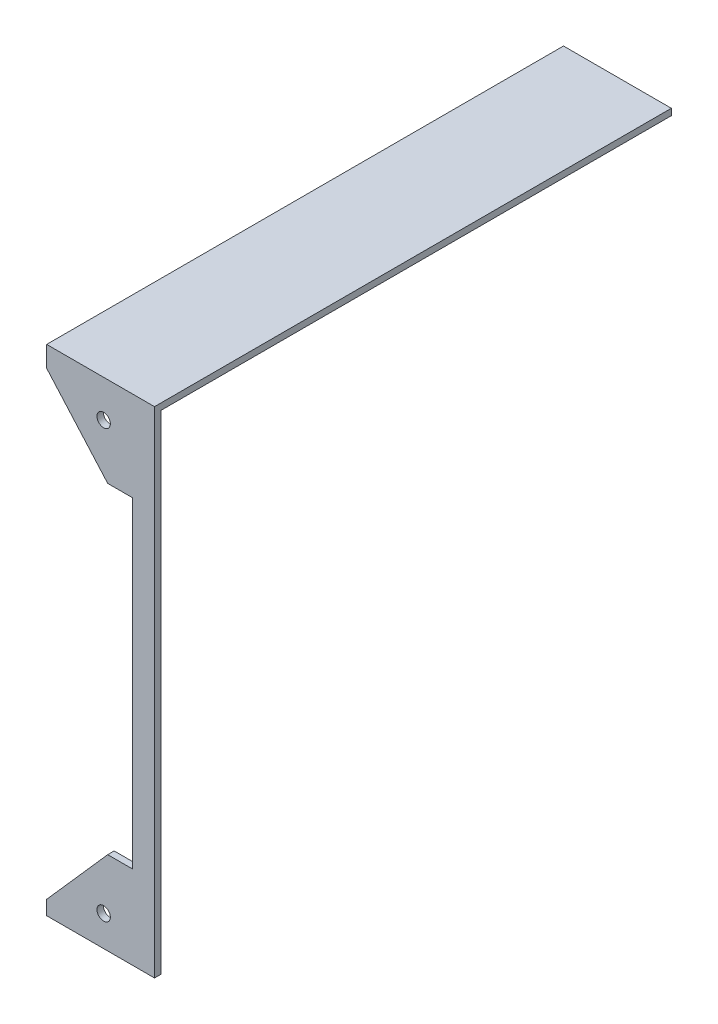
SolidWorks part; units mm, degrees
ref_plane "Front Plane" through (0, 0, 0) normal (0, 0, 1) x (1, 0, 0)
ref_plane "Top Plane" through (0, 0, 0) normal (0, 1, 0) x (1, 0, 0)
ref_plane "Right Plane" through (0, 0, 0) normal (1, 0, 0) x (0, 0, -1)
sketch "Sketch1" plane through (0, 0, 0) normal (0, 0, 1) x (1, 0, 0)
  line L0 (-250, 120) -> (0, 120) construction
  line L1 (0, 118) -> (0, 2) construction
  line L2 (0, 0) -> (-250, 0) construction
  line L3 (-26.5, 116.5) -> (-11.5, 99.5) construction
  line L4 (-11.5, 99.5) -> (-5.4, 99.5) construction
  line L5 (-5.4, 99.5) -> (-5.4, 20.5) construction
  line L6 (-11.5, 20.5) -> (-26.5, 3.5) construction
  line L7 (-5.4, 20.5) -> (-11.5, 20.5) construction
  line L8 (-26.5, 120) -> (0, 120)
  line L9 (0, 120) -> (0, 0)
  line L10 (0, 0) -> (-26.5, 0)
  line L11 (-26.5, 116.5) -> (-11.5, 99.5)
  line L12 (-11.5, 99.5) -> (-5.4, 99.5)
  line L13 (-5.4, 99.5) -> (-5.4, 20.5)
  line L14 (-11.5, 20.5) -> (-26.5, 3.5)
  line L15 (-5.4, 20.5) -> (-11.5, 20.5)
  line L16 (-26.5, 3.5) -> (-26.5, 0)
  line L17 (-26.5, 116.5) -> (-26.5, 120)
  arc A0 (-14.15, 112.5) -> (-10.85, 112.5) centre (-12.5, 112.5) ccw construction
  arc A1 (-10.85, 112.5) -> (-14.15, 112.5) centre (-12.5, 112.5) ccw construction
  arc A2 (-14.15, 7.5) -> (-10.85, 7.5) centre (-12.5, 7.5) ccw construction
  arc A3 (-10.85, 7.5) -> (-14.15, 7.5) centre (-12.5, 7.5) ccw construction
  arc A4 (-14.15, 112.5) -> (-10.85, 112.5) centre (-12.5, 112.5) ccw
  arc A5 (-10.85, 112.5) -> (-14.15, 112.5) centre (-12.5, 112.5) ccw
  arc A6 (-14.15, 7.5) -> (-10.85, 7.5) centre (-12.5, 7.5) ccw
  arc A7 (-10.85, 7.5) -> (-14.15, 7.5) centre (-12.5, 7.5) ccw
extrude "Boss-Extrude1" add sketch "Sketch1" along normal blind 1.5875
sketch "Sketch2" plane through (0, 120, 0) normal (0, 1, 0) x (1, 0, 0)
  line L0 (0, -1.5875) -> (0, 125.4125)
  line L1 (0, 125.4125) -> (-26.5, 125.4125)
  line L2 (-26.5, 125.4125) -> (-26.5, -1.5875)
  line L3 (0, -1.5875) -> (-26.5, -1.5875)
  dimension "D1" = 127
extrude "Boss-Extrude2" add sketch "Sketch2" along normal blind 1.5875
